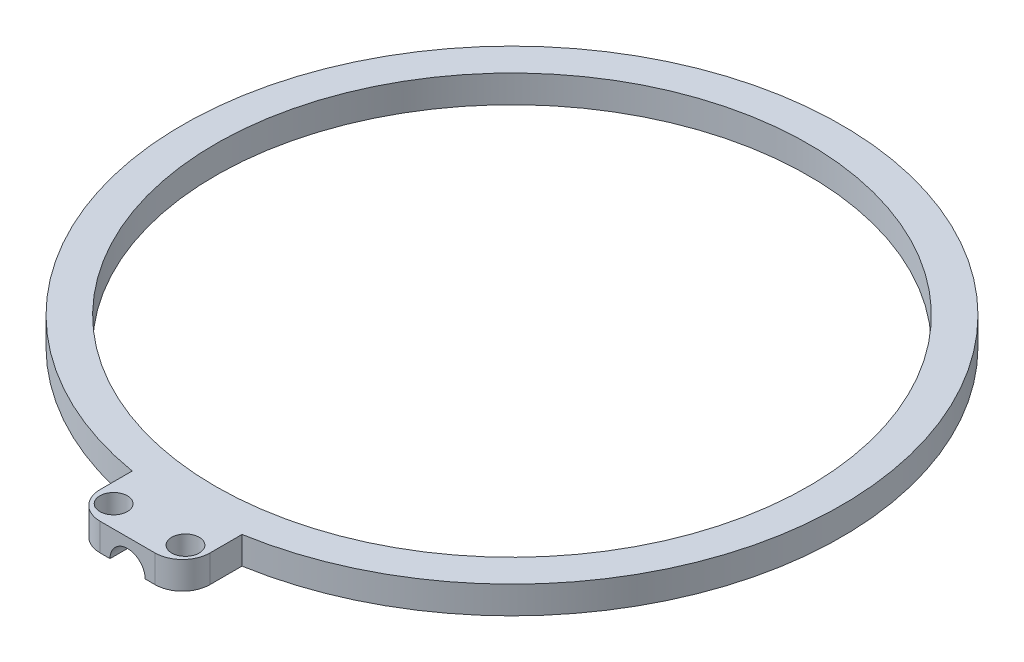
SolidWorks part; units mm, degrees
material "PE High Density Film"
ref_plane "Front" through (0, 0, 0) normal (0, 0, 1) x (1, 0, 0)
ref_plane "Top" through (0, 0, 0) normal (0, 1, 0) x (1, 0, 0)
ref_plane "Right" through (0, 0, 0) normal (1, 0, 0) x (0, 0, -1)
sketch "Sketch1" plane through (0, 0, 0) normal (0, 1, 0) x (1, 0, 0)
  circle A0 centre (0, 0) radius 68.58
  circle A1 centre (0, 0) radius 76.2
  dimension "D1" = 152.4
  dimension "D2" = 7.62
extrude "Boss-Extrude1" add sketch "Sketch1" along normal mid plane 6.35
sketch "Sketch2" plane through (0, 3.175, 0) normal (0, 1, 0) x (1, 0, 0)
  line L0 (0, 0) -> (0, -76.2) construction
  line L2 (-12.7, -88.9) -> (-12.7, -75.1342)
  line L3 (-12.7, -88.9) -> (12.7, -88.9)
  line L4 (12.7, -88.9) -> (12.7, -75.1342)
  circle A0 centre (0, 0) radius 76.2 construction
  arc A1 (-12.7, -75.1342) -> (12.7, -75.1342) centre (0, 0) ccw
  dimension "D1" = 12.7
  dimension "D2" = 25.4
extrude "Boss-Extrude2" add sketch "Sketch2" against normal blind 6.35
fillet "Fillet1" radius 6.35 2 edges at (12.7, 0, 88.9) (-12.7, 0, 88.9)
sketch "Sketch3" plane through (0, 0, 88.9) normal (0, 0, 1) x (1, 0, 0)
  line L0 (0, 3.175) -> (0, -3.175) construction
  line L1 (-6.35, 3.175) -> (6.35, 3.175) construction
  line L2 (-6.35, -3.175) -> (6.35, -3.175) construction
  line L3 (-4.064, -3.175) -> (4.064, -3.175)
  arc A0 (4.064, -3.175) -> (-4.064, -3.175) centre (0, -3.175) ccw
  dimension "D1" = 4.064
extrude "Cut-Extrude1" cut sketch "Sketch3" against normal blind 11.43
hole_wizard "3/8 (0.25) Diameter Hole2" positions "3DSketch2" profile "Sketch5" hole size "3/8" standard "ANSI Inch" end condition through all
sketch3d "3DSketch2"
  line L0 (-12.7, -3.175, 75.1342) -> (-12.7, -3.175, 82.55) construction
  line L1 (-6.35, -3.175, 88.9) -> (-4.064, -3.175, 88.9) construction
  line L2 (12.7, -3.175, 82.55) -> (12.7, -3.175, 75.1342) construction
  line L3 (4.064, -3.175, 88.9) -> (6.35, -3.175, 88.9) construction
  point P0 (-8.3058, -3.175, 83.82)
  point P2 (8.3058, -3.175, 83.82)
  dimension "D1" = 4.3942
  dimension "D2" = 5.08
  dimension "D3" = 4.3942
  dimension "D4" = 5.08
sketch "Sketch5" plane through (-8.3058, -3.175, 83.82) normal (1, 0, 0) x (0, 0, -1)
  line L0 (0, 0) -> (0, 6.35)
  line L1 (0, 6.35) -> (3.175, 6.35)
  line L2 (3.175, 6.35) -> (3.175, 0)
  line L5 (3.175, 0) -> (0, 0)
  line L11 (0, -6.35) -> (0, 107.95) construction
  dimension "Thru Hole Dia." = 6.35
  dimension "Thru Hole Depth" = 6.35
